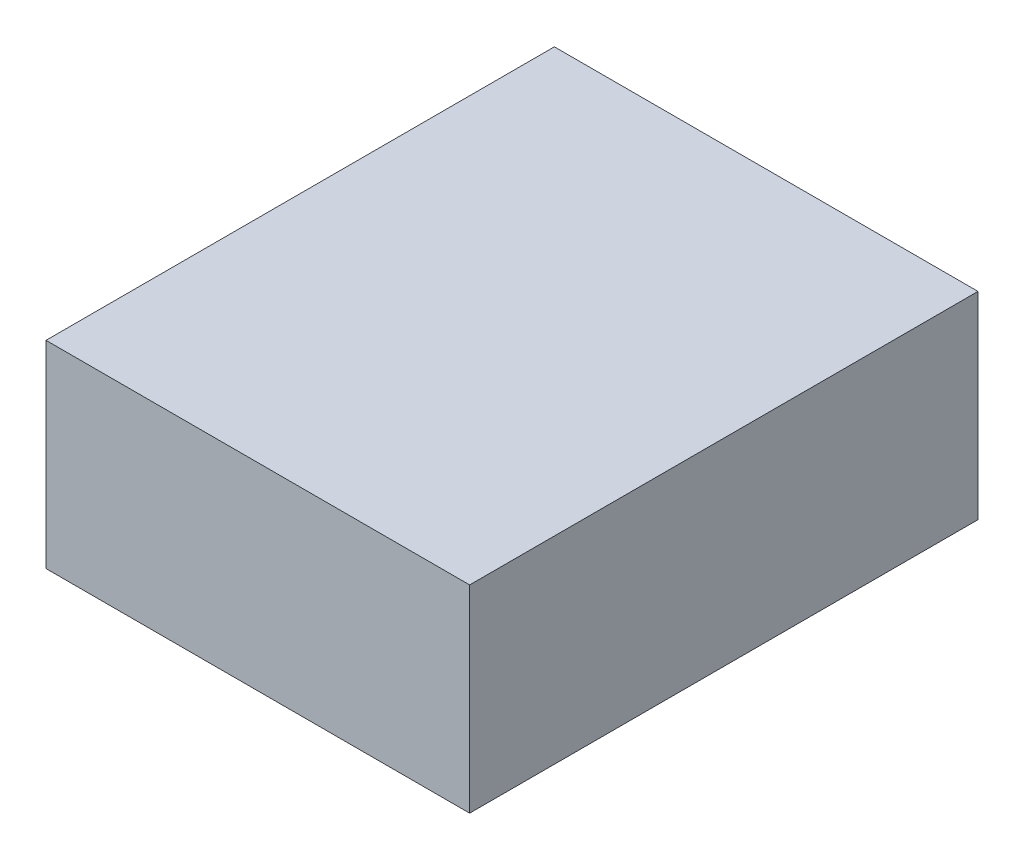
SolidWorks part; units mm, degrees
other "base"
ref_plane "Front Plane" through (0, 0, 0) normal (0, 0, 1) x (1, 0, 0)
ref_plane "Top Plane" through (0, 0, 0) normal (0, 1, 0) x (1, 0, 0)
ref_plane "Right Plane" through (0, 0, 0) normal (1, 0, 0) x (0, 0, -1)
sketch "Sketch2" plane through (0, 0, 0) normal (0, 1, 0) x (1, 0, 0)
  line L5 (-75, 90) -> (75, 90)
  line L6 (-75, 90) -> (-75, -90)
  line L7 (-75, -90) -> (75, -90)
  line L8 (75, 90) -> (75, -90)
  line L9 (-75, 90) -> (75, -90) construction
  line L10 (-75, -90) -> (75, 90) construction
  point P0 (0, 0)
  dimension "D1" = 150
  dimension "D2" = 180
extrude "Boss-Extrude1" add sketch "Sketch2" along normal blind 70
